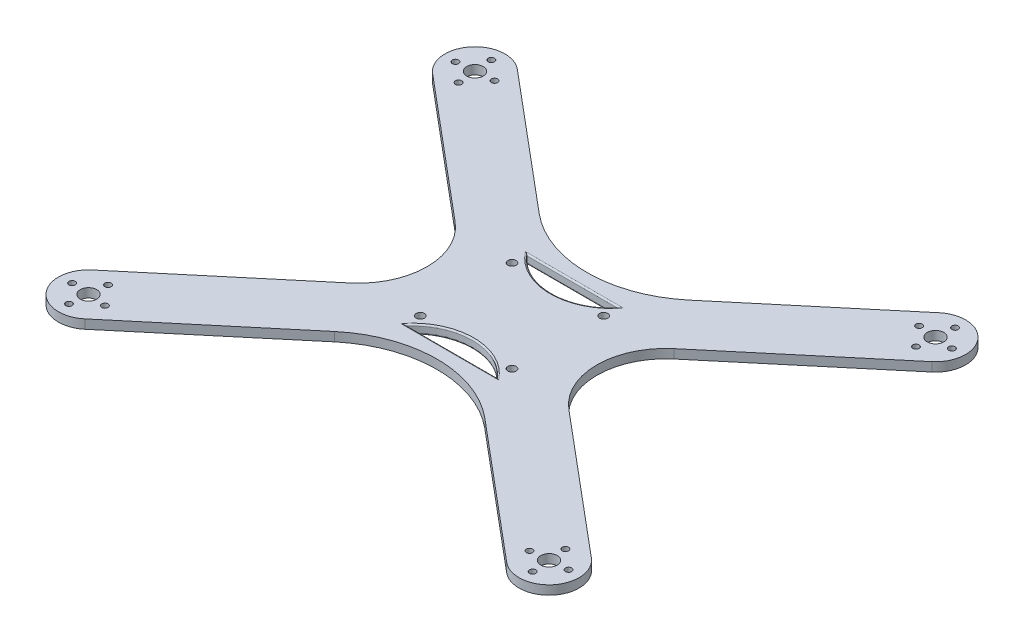
SolidWorks part; units mm, degrees
ref_plane "Front Plane" through (0, 0, 0) normal (0, 0, 1) x (1, 0, 0)
ref_plane "Top Plane" through (0, 0, 0) normal (0, 1, 0) x (1, 0, 0)
ref_plane "Right Plane" through (0, 0, 0) normal (1, 0, 0) x (0, 0, -1)
sketch "Sketch1" plane through (0, 0, 0) normal (0, 1, 0) x (1, 0, 0)
  line L1 (-36.375, -26.375) -> (36.375, -26.375) construction
  line L2 (-36.375, -26.375) -> (-36.375, 26.375) construction
  line L3 (-36.375, 26.375) -> (36.375, 26.375) construction
  line L4 (36.375, -26.375) -> (36.375, 26.375) construction
  line L5 (-36.375, -26.375) -> (36.375, 26.375) construction
  line L6 (-36.375, 26.375) -> (36.375, -26.375) construction
  circle A0 centre (-36.375, 26.375) radius 1.25
  circle A4 centre (36.375, 26.375) radius 1.25
  circle A5 centre (36.375, -26.375) radius 1.25
  circle A6 centre (-36.375, -26.375) radius 1.25
  point P8 (0, 0)
  dimension "D1" = 2.5
  dimension "D2" = 52.75
  dimension "D3" = 72.75
sketch "Sketch2" plane through (0, 0, 0) normal (0, 1, 0) x (1, 0, 0)
  line L0 (0, 0) -> (-76.6044, 64.2788) construction
  line L1 (0, 0) -> (76.6044, 64.2788) construction
  line L2 (0, 0) -> (76.6044, -64.2788) construction
  line L3 (0, 0) -> (-76.6044, -64.2788) construction
  line L4 (-30, 0) -> (30, 0) construction
  line L5 (-70.1766, 71.9392) -> (-83.0323, 56.6183) construction
  line L10 (36.4129, -30.5541) -> (-32.6921, 27.4319) construction
  line L11 (36.4129, 34.0316) -> (-32.6921, -30.5541) construction
  line L12 (0, 21.0062) -> (0, -21.0062) construction
  line L13 (-83.0323, 56.6183) -> (-36.4129, 17.5)
  line L14 (83.0323, -56.6183) -> (36.4129, -17.5)
  line L15 (-82.5816, 63.7558) -> (-70.6273, 64.8017) construction
  line L16 (-77.1274, 70.2559) -> (-76.0815, 58.3016) construction
  line L17 (-83.0323, -56.6183) -> (-70.1766, -71.9392) construction
  line L18 (-83.0323, -56.6183) -> (-36.4129, -17.5)
  line L19 (-70.1766, -71.9392) -> (-25, -34.0316)
  line L20 (36.4129, 34.0316) -> (-32.6921, 27.4319) construction
  line L21 (25, 34.0316) -> (70.1766, 71.9392)
  line L22 (-25, 34.0316) -> (-70.1766, 71.9392)
  line L23 (36.4129, 17.5) -> (83.0323, 56.6183)
  line L24 (25, -34.0316) -> (70.1766, -71.9392)
  line L25 (-32.6921, 27.4319) -> (-32.6921, -30.5541) construction
  line L26 (-32.6921, -30.5541) -> (36.4129, -30.5541) construction
  line L27 (36.4129, -30.5541) -> (36.4129, 34.0316) construction
  arc A3 (-70.1766, 71.9392) -> (-83.0323, 56.6183) centre (-76.6044, 64.2788) ccw
  circle A4 centre (-77.1274, 70.2559) radius 1.05
  circle A5 centre (-70.6273, 64.8017) radius 1.05
  circle A6 centre (-76.0815, 58.3016) radius 1.05
  circle A7 centre (-82.5816, 63.7558) radius 1.05
  circle A8 centre (-76.6044, 64.2788) radius 2.75
  circle A9 centre (-77.1274, -70.2559) radius 1.05
  circle A10 centre (-76.0815, -58.3016) radius 1.05
  circle A11 centre (-82.5816, -63.7558) radius 1.05
  circle A12 centre (-76.6044, -64.2788) radius 2.75
  circle A13 centre (-70.6273, -64.8017) radius 1.05
  arc A14 (-70.1766, -71.9392) -> (-83.0323, -56.6183) centre (-76.6044, -64.2788) cw
  arc A15 (70.1766, -71.9392) -> (83.0323, -56.6183) centre (76.6044, -64.2788) ccw
  circle A16 centre (70.6273, -64.8017) radius 1.05
  circle A17 centre (76.6044, -64.2788) radius 2.75
  circle A18 centre (82.5816, -63.7558) radius 1.05
  circle A19 centre (76.0815, -58.3016) radius 1.05
  circle A20 centre (77.1274, -70.2559) radius 1.05
  circle A21 centre (76.6044, 64.2788) radius 2.75
  circle A22 centre (82.5816, 63.7558) radius 1.05
  circle A23 centre (76.0815, 58.3016) radius 1.05
  circle A24 centre (70.6273, 64.8017) radius 1.05
  circle A25 centre (77.1274, 70.2559) radius 1.05
  arc A26 (70.1766, 71.9392) -> (83.0323, 56.6183) centre (76.6044, 64.2788) cw
  arc A27 (-36.4129, 17.5) -> (-36.4129, -17.5) centre (-51.0972, 0) cw
  arc A28 (-25, -34.0316) -> (25, -34.0316) centre (0, -63.8254) cw
  arc A29 (36.4129, -17.5) -> (36.4129, 17.5) centre (51.0972, 0) cw
  arc A30 (25, 34.0316) -> (-25, 34.0316) centre (0, 63.8254) cw
  point P29 (-76.6044, 64.2788)
  point P34 (-76.6044, 64.2788)
  point P35 (-76.6044, 64.2788)
  point P61 (76.6044, 64.2788)
  point P63 (0, 0)
  dimension "D5" = 20
  dimension "D7" = 2.1
  dimension "D10" = 5.5
  dimension "D2" = 50
  dimension "D3" = 40
  dimension "D4" = 100
  dimension "D6" = 35
  dimension "D8" = 12
  dimension "D9" = 45
extrude "Boss-Extrude2" add sketch "Sketch2" along normal blind 3
sketch "Sketch4" plane through (0, 0, 0) normal (0, 1, 0) x (1, 0, 0)
  line L1 (-15.25, -15.25) -> (15.25, -15.25) construction
  line L2 (-15.25, -15.25) -> (-15.25, 15.25) construction
  line L3 (-15.25, 15.25) -> (15.25, 15.25) construction
  line L4 (15.25, -15.25) -> (15.25, 15.25) construction
  line L5 (-15.25, -15.25) -> (15.25, 15.25) construction
  line L6 (-15.25, 15.25) -> (15.25, -15.25) construction
  circle A0 centre (-15.25, 15.25) radius 1.375
  circle A1 centre (15.25, -15.25) radius 1.375
  circle A2 centre (-15.25, -15.25) radius 1.375
  circle A3 centre (15.25, 15.25) radius 1.375
  point P5 (0, 0)
  dimension "D2" = 2.75
  dimension "D1" = 30.5
extrude "Cut-Extrude1" cut sketch "Sketch4" along normal blind 3
sketch "Sketch5" plane through (0, 3, 0) normal (0, 1, 0) x (1, 0, 0)
  line L0 (-15.25, 13.875) -> (-15.25, 20.25) construction
  line L1 (-15.25, 20.25) -> (15.25, 20.25)
  line L2 (15.25, 20.25) -> (15.25, 13.875) construction
  line L3 (-15.25, 13.875) -> (15.25, 13.875) construction
  line L4 (-20.7888, 0) -> (21.3614, 0) construction
  line L5 (-15.25, -20.25) -> (15.25, -20.25)
  circle A0 centre (-15.25, 15.25) radius 1.375 construction
  circle A1 centre (15.25, 15.25) radius 1.375 construction
  arc A2 (-15.25, 20.25) -> (15.25, 20.25) centre (0, 33.1898) ccw
  arc A5 (-15.25, -20.25) -> (15.25, -20.25) centre (0, -33.1898) cw
  dimension "D1" = 5
  dimension "D2" = 20
extrude "Cut-Extrude2" cut sketch "Sketch5" against normal blind 3
fillet "Fillet3" radius 0.5 8 edges at (0, 3, 20.25) (0, 3, 13.1898) (0, 0, 20.25) (0, 0, 13.1898) (0, 0, -13.1898) (0, 0, -20.25) (0, 3, -13.1898) (0, 3, -20.25)
